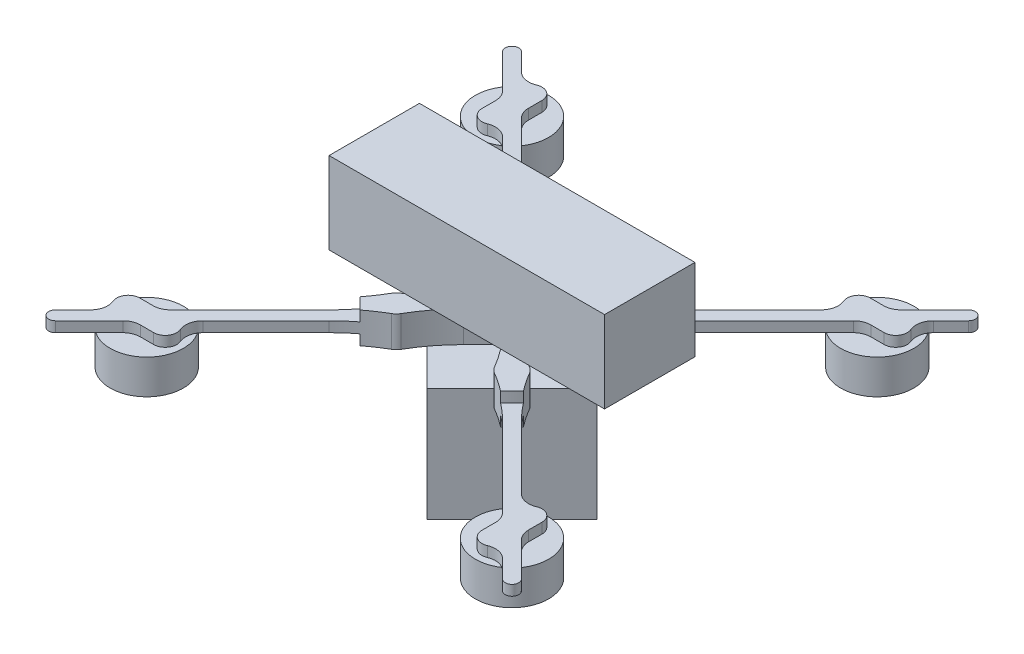
SolidWorks part; units mm, degrees
other "Markup1"
sketch "Sketch7" plane through (54.583, -16.8, -54.583) normal (0.6495, -0.6416, -0.408) x (0.4889, -0.0586, 0.8704)
ref_plane "Front Plane" through (0, 0, 0) normal (0, 0, 1) x (1, 0, 0)
ref_plane "Top Plane" through (0, 0, 0) normal (0, 1, 0) x (1, 0, 0)
ref_plane "Right Plane" through (0, 0, 0) normal (1, 0, 0) x (0, 0, -1)
sketch "Sketch1" plane through (0, 0, 0) normal (0, 1, 0) x (1, 0, 0)
  line L0 (0, 0) -> (0, 62.3643) construction
  line L1 (0, 0) -> (-42.4264, 42.4264) construction
  line L4 (-42.4264, 46.7264) -> (-42.4264, 38.1264) construction
  line L5 (0, 2.192) -> (-51.937, 54.129)
  line L6 (-2.192, 0) -> (-42.9431, 40.751)
  line L7 (-1.096, -1.096) -> (-43.5224, 41.3304) construction
  line L8 (1.096, 1.096) -> (-41.3304, 43.5224) construction
  line L9 (-39.7514, 46.7264) -> (-39.7514, 41.9434)
  line L10 (-45.1014, 38.1264) -> (-45.1014, 42.9094)
  line L11 (-45.1014, 42.9094) -> (-54.129, 51.937)
  line L12 (0, 2.192) -> (0, 0)
  line L13 (0, 0) -> (-2.192, 0)
  arc A2 (-42.4264, 44.0514) -> (-45.051, 47.2431) centre (-42.4264, 46.7264) ccw
  circle A3 centre (-42.4264, 38.1264) radius 2.675
  arc A4 (-51.937, 54.129) -> (-54.129, 51.937) centre (-53.033, 53.033) ccw
  circle A5 centre (-13.435, 13.435) radius 3
  point P6 (-42.4264, 42.4264)
  dimension "D7" = 5.35
  dimension "D8" = 6
  dimension "D1" = 60
  dimension "D2" = 45
  dimension "D3" = 8.6
  dimension "D4" = 1.55
  dimension "D5" = 1.55
  dimension "D6" = 75
  dimension "D9" = 41
extrude "Boss-Extrude1" add sketch "Sketch1" along normal blind 2.4
sketch "Sketch6" plane through (0, 0, 0) normal (0, -1, 0) x (1, 0, 0)
  circle A0 centre (-42.4264, -42.4264) radius 8.5
  dimension "D1" = 17
extrude "Boss-Extrude5" add sketch "Sketch6" along normal blind 8 separate body
fillet "Fillet1" radius 4 4 edges at (-39.7514, 1.2, -41.9434) (-45.051, 1.2, -47.2431) (-45.1014, 1.2, -42.9094) (-39.8018, 1.2, -37.6097)
fillet "Fillet2" radius 40 4 edges at (-10.5228, 1.2, -12.7148) (-14.1553, 1.2, -16.3473) (-12.7148, 1.2, -10.5228) (-16.3473, 1.2, -14.1553)
pattern_circular "CirPattern3" count 4 over 360 about axis through (0, 0, 0) along (0, 1, 0) of bodies 106
pattern_circular "CirPattern1" count 4 over 360 about axis through (0, 0, 0) along (0, 1, 0) of "Boss-Extrude1", "Fillet2", "Fillet1"
sketch "Sketch3" plane through (0, 2.4, 0) normal (0, 1, 0) x (1, 0, 0)
  line L10 (-2.192, 0) -> (-6.7017, -4.5097)
  line L12 (-2.192, 0) -> (-6.7017, -4.5097)
  line L32 (0, 2.192) -> (-4.5097, 6.7017)
  line L33 (-20.1684, 22.3604) -> (-38.5798, 40.7719)
  line L34 (-39.7514, 43.6003) -> (-39.7514, 46.7264)
  line L35 (-47.8541, 50.0461) -> (-51.937, 54.129)
  line L36 (-54.129, 51.937) -> (-46.273, 44.0809)
  line L37 (-45.1014, 41.2525) -> (-45.1014, 38.1264)
  line L38 (-36.9987, 34.8067) -> (-22.3604, 20.1684)
  line L39 (-6.7017, 4.5097) -> (-2.192, 0)
  line L44 (-22.3604, -20.1684) -> (-40.7719, -38.5798)
  line L45 (-22.3604, -20.1684) -> (-40.7719, -38.5798)
  line L46 (-43.6003, -39.7514) -> (-46.7264, -39.7514)
  line L47 (-43.6003, -39.7514) -> (-46.7264, -39.7514)
  line L48 (-50.0461, -47.8541) -> (-54.129, -51.937)
  line L49 (-50.0461, -47.8541) -> (-54.129, -51.937)
  line L50 (-51.937, -54.129) -> (-44.0809, -46.273)
  line L51 (-51.937, -54.129) -> (-44.0809, -46.273)
  line L52 (-41.2525, -45.1014) -> (-38.1264, -45.1014)
  line L53 (-41.2525, -45.1014) -> (-38.1264, -45.1014)
  line L54 (-34.8067, -36.9987) -> (-20.1684, -22.3604)
  line L55 (-34.8067, -36.9987) -> (-20.1684, -22.3604)
  line L56 (-4.5097, -6.7017) -> (0, -2.192)
  line L57 (-4.5097, -6.7017) -> (0, -2.192)
  line L58 (0, -2.192) -> (4.5097, -6.7017)
  line L59 (0, -2.192) -> (4.5097, -6.7017)
  line L60 (20.1684, -22.3604) -> (38.5798, -40.7719)
  line L61 (20.1684, -22.3604) -> (38.5798, -40.7719)
  line L62 (39.7514, -43.6003) -> (39.7514, -46.7264)
  line L63 (39.7514, -43.6003) -> (39.7514, -46.7264)
  line L64 (0, 2.192) -> (-4.5097, 6.7017)
  line L65 (-20.1684, 22.3604) -> (-38.5798, 40.7719)
  line L66 (-39.7514, 43.6003) -> (-39.7514, 46.7264)
  line L67 (-47.8541, 50.0461) -> (-51.937, 54.129)
  line L68 (-54.129, 51.937) -> (-46.273, 44.0809)
  line L69 (-45.1014, 41.2525) -> (-45.1014, 38.1264)
  line L70 (-36.9987, 34.8067) -> (-22.3604, 20.1684)
  line L71 (-6.7017, 4.5097) -> (-2.192, 0)
  line L96 (47.8541, -50.0461) -> (51.937, -54.129)
  line L97 (47.8541, -50.0461) -> (51.937, -54.129)
  line L98 (54.129, -51.937) -> (46.273, -44.0809)
  line L99 (54.129, -51.937) -> (46.273, -44.0809)
  line L100 (45.1014, -41.2525) -> (45.1014, -38.1264)
  line L101 (45.1014, -41.2525) -> (45.1014, -38.1264)
  line L102 (36.9987, -34.8067) -> (22.3604, -20.1684)
  line L103 (36.9987, -34.8067) -> (22.3604, -20.1684)
  line L104 (6.7017, -4.5097) -> (2.192, 0)
  line L105 (6.7017, -4.5097) -> (2.192, 0)
  line L106 (2.192, 0) -> (6.7017, 4.5097)
  line L107 (2.192, 0) -> (6.7017, 4.5097)
  line L108 (22.3604, 20.1684) -> (40.7719, 38.5798)
  line L109 (22.3604, 20.1684) -> (40.7719, 38.5798)
  line L110 (43.6003, 39.7514) -> (46.7264, 39.7514)
  line L111 (43.6003, 39.7514) -> (46.7264, 39.7514)
  line L112 (50.0461, 47.8541) -> (54.129, 51.937)
  line L113 (50.0461, 47.8541) -> (54.129, 51.937)
  line L114 (51.937, 54.129) -> (44.0809, 46.273)
  line L115 (51.937, 54.129) -> (44.0809, 46.273)
  line L116 (41.2525, 45.1014) -> (38.1264, 45.1014)
  line L117 (41.2525, 45.1014) -> (38.1264, 45.1014)
  line L118 (34.8067, 36.9987) -> (20.1684, 22.3604)
  line L119 (34.8067, 36.9987) -> (20.1684, 22.3604)
  line L120 (4.5097, 6.7017) -> (0, 2.192)
  line L121 (4.5097, 6.7017) -> (0, 2.192)
  circle A0 centre (0, 0) radius 25.002
  arc A53 (-10.839, 14.9386) -> (-4.5097, 6.7017) centre (23.7746, 34.986) ccw
  arc A54 (-10.839, 14.9386) -> (-11.9315, 16.0311) centre (-13.435, 13.435) ccw
  arc A55 (-20.1684, 22.3604) -> (-11.9315, 16.0311) centre (8.1159, 50.6447) ccw
  arc A56 (-39.7514, 43.6003) -> (-38.5798, 40.7719) centre (-35.7514, 43.6003) ccw
  arc A57 (-39.7514, 46.7264) -> (-43.4681, 49.1903) centre (-42.4264, 46.7264) ccw
  arc A58 (-47.8541, 50.0461) -> (-43.4681, 49.1903) centre (-45.0257, 52.8745) ccw
  arc A59 (-51.937, 54.129) -> (-54.129, 51.937) centre (-53.033, 53.033) ccw
  arc A60 (-45.1014, 41.2525) -> (-46.273, 44.0809) centre (-49.1014, 41.2525) ccw
  arc A61 (-45.1014, 38.1264) -> (-41.3848, 35.6625) centre (-42.4264, 38.1264) ccw
  arc A62 (-36.9987, 34.8067) -> (-41.3848, 35.6625) centre (-39.8272, 31.9783) ccw
  arc A63 (-16.0311, 11.9315) -> (-22.3604, 20.1684) centre (-50.6447, -8.1159) ccw
  arc A64 (-16.0311, 11.9315) -> (-14.9386, 10.839) centre (-13.435, 13.435) ccw
  arc A65 (-6.7017, 4.5097) -> (-14.9386, 10.839) centre (-34.986, -23.7746) ccw
  arc A66 (-14.9386, -10.839) -> (-6.7017, -4.5097) centre (-34.986, 23.7746) ccw
  arc A67 (-14.9386, -10.839) -> (-6.7017, -4.5097) centre (-34.986, 23.7746) ccw
  arc A68 (-14.9386, -10.839) -> (-16.0311, -11.9315) centre (-13.435, -13.435) ccw
  arc A69 (-14.9386, -10.839) -> (-16.0311, -11.9315) centre (-13.435, -13.435) ccw
  arc A70 (-22.3604, -20.1684) -> (-16.0311, -11.9315) centre (-50.6447, 8.1159) ccw
  arc A71 (-22.3604, -20.1684) -> (-16.0311, -11.9315) centre (-50.6447, 8.1159) ccw
  arc A72 (-43.6003, -39.7514) -> (-40.7719, -38.5798) centre (-43.6003, -35.7514) ccw
  arc A73 (-43.6003, -39.7514) -> (-40.7719, -38.5798) centre (-43.6003, -35.7514) ccw
  arc A74 (-46.7264, -39.7514) -> (-49.1903, -43.4681) centre (-46.7264, -42.4264) ccw
  arc A75 (-46.7264, -39.7514) -> (-49.1903, -43.4681) centre (-46.7264, -42.4264) ccw
  arc A76 (-50.0461, -47.8541) -> (-49.1903, -43.4681) centre (-52.8745, -45.0257) ccw
  arc A77 (-50.0461, -47.8541) -> (-49.1903, -43.4681) centre (-52.8745, -45.0257) ccw
  arc A78 (-54.129, -51.937) -> (-51.937, -54.129) centre (-53.033, -53.033) ccw
  arc A79 (-54.129, -51.937) -> (-51.937, -54.129) centre (-53.033, -53.033) ccw
  arc A80 (-41.2525, -45.1014) -> (-44.0809, -46.273) centre (-41.2525, -49.1014) ccw
  arc A81 (-41.2525, -45.1014) -> (-44.0809, -46.273) centre (-41.2525, -49.1014) ccw
  arc A82 (-38.1264, -45.1014) -> (-35.6625, -41.3848) centre (-38.1264, -42.4264) ccw
  arc A83 (-38.1264, -45.1014) -> (-35.6625, -41.3848) centre (-38.1264, -42.4264) ccw
  arc A84 (-34.8067, -36.9987) -> (-35.6625, -41.3848) centre (-31.9783, -39.8272) ccw
  arc A85 (-34.8067, -36.9987) -> (-35.6625, -41.3848) centre (-31.9783, -39.8272) ccw
  arc A86 (-11.9315, -16.0311) -> (-20.1684, -22.3604) centre (8.1159, -50.6447) ccw
  arc A87 (-11.9315, -16.0311) -> (-20.1684, -22.3604) centre (8.1159, -50.6447) ccw
  arc A88 (-11.9315, -16.0311) -> (-10.839, -14.9386) centre (-13.435, -13.435) ccw
  arc A89 (-11.9315, -16.0311) -> (-10.839, -14.9386) centre (-13.435, -13.435) ccw
  arc A90 (-4.5097, -6.7017) -> (-10.839, -14.9386) centre (23.7746, -34.986) ccw
  arc A91 (-4.5097, -6.7017) -> (-10.839, -14.9386) centre (23.7746, -34.986) ccw
  arc A92 (10.839, -14.9386) -> (4.5097, -6.7017) centre (-23.7746, -34.986) ccw
  arc A93 (10.839, -14.9386) -> (4.5097, -6.7017) centre (-23.7746, -34.986) ccw
  arc A94 (10.839, -14.9386) -> (11.9315, -16.0311) centre (13.435, -13.435) ccw
  arc A95 (10.839, -14.9386) -> (11.9315, -16.0311) centre (13.435, -13.435) ccw
  arc A96 (20.1684, -22.3604) -> (11.9315, -16.0311) centre (-8.1159, -50.6447) ccw
  arc A97 (20.1684, -22.3604) -> (11.9315, -16.0311) centre (-8.1159, -50.6447) ccw
  arc A98 (39.7514, -43.6003) -> (38.5798, -40.7719) centre (35.7514, -43.6003) ccw
  arc A99 (39.7514, -43.6003) -> (38.5798, -40.7719) centre (35.7514, -43.6003) ccw
  arc A100 (39.7514, -46.7264) -> (43.4681, -49.1903) centre (42.4264, -46.7264) ccw
  arc A101 (39.7514, -46.7264) -> (43.4681, -49.1903) centre (42.4264, -46.7264) ccw
  arc A102 (47.8541, -50.0461) -> (43.4681, -49.1903) centre (45.0257, -52.8745) ccw
  arc A103 (47.8541, -50.0461) -> (43.4681, -49.1903) centre (45.0257, -52.8745) ccw
  arc A104 (51.937, -54.129) -> (54.129, -51.937) centre (53.033, -53.033) ccw
  arc A105 (-10.839, 14.9386) -> (-4.5097, 6.7017) centre (23.7746, 34.986) ccw
  arc A106 (-10.839, 14.9386) -> (-11.9315, 16.0311) centre (-13.435, 13.435) ccw
  arc A107 (-20.1684, 22.3604) -> (-11.9315, 16.0311) centre (8.1159, 50.6447) ccw
  arc A108 (-39.7514, 43.6003) -> (-38.5798, 40.7719) centre (-35.7514, 43.6003) ccw
  arc A109 (-39.7514, 46.7264) -> (-43.4681, 49.1903) centre (-42.4264, 46.7264) ccw
  arc A110 (-47.8541, 50.0461) -> (-43.4681, 49.1903) centre (-45.0257, 52.8745) ccw
  arc A111 (-51.937, 54.129) -> (-54.129, 51.937) centre (-53.033, 53.033) ccw
  arc A112 (-45.1014, 41.2525) -> (-46.273, 44.0809) centre (-49.1014, 41.2525) ccw
  arc A113 (-45.1014, 38.1264) -> (-41.3848, 35.6625) centre (-42.4264, 38.1264) ccw
  arc A114 (-36.9987, 34.8067) -> (-41.3848, 35.6625) centre (-39.8272, 31.9783) ccw
  arc A115 (-16.0311, 11.9315) -> (-22.3604, 20.1684) centre (-50.6447, -8.1159) ccw
  arc A116 (-16.0311, 11.9315) -> (-14.9386, 10.839) centre (-13.435, 13.435) ccw
  arc A117 (-6.7017, 4.5097) -> (-14.9386, 10.839) centre (-34.986, -23.7746) ccw
  arc A157 (51.937, -54.129) -> (54.129, -51.937) centre (53.033, -53.033) ccw
  arc A158 (45.1014, -41.2525) -> (46.273, -44.0809) centre (49.1014, -41.2525) ccw
  arc A159 (45.1014, -41.2525) -> (46.273, -44.0809) centre (49.1014, -41.2525) ccw
  arc A160 (45.1014, -38.1264) -> (41.3848, -35.6625) centre (42.4264, -38.1264) ccw
  arc A161 (45.1014, -38.1264) -> (41.3848, -35.6625) centre (42.4264, -38.1264) ccw
  arc A162 (36.9987, -34.8067) -> (41.3848, -35.6625) centre (39.8272, -31.9783) ccw
  arc A163 (36.9987, -34.8067) -> (41.3848, -35.6625) centre (39.8272, -31.9783) ccw
  arc A164 (16.0311, -11.9315) -> (22.3604, -20.1684) centre (50.6447, 8.1159) ccw
  arc A165 (16.0311, -11.9315) -> (22.3604, -20.1684) centre (50.6447, 8.1159) ccw
  arc A166 (16.0311, -11.9315) -> (14.9386, -10.839) centre (13.435, -13.435) ccw
  arc A167 (16.0311, -11.9315) -> (14.9386, -10.839) centre (13.435, -13.435) ccw
  arc A168 (6.7017, -4.5097) -> (14.9386, -10.839) centre (34.986, 23.7746) ccw
  arc A169 (6.7017, -4.5097) -> (14.9386, -10.839) centre (34.986, 23.7746) ccw
  arc A170 (14.9386, 10.839) -> (6.7017, 4.5097) centre (34.986, -23.7746) ccw
  arc A171 (14.9386, 10.839) -> (6.7017, 4.5097) centre (34.986, -23.7746) ccw
  arc A172 (14.9386, 10.839) -> (16.0311, 11.9315) centre (13.435, 13.435) ccw
  arc A173 (14.9386, 10.839) -> (16.0311, 11.9315) centre (13.435, 13.435) ccw
  arc A174 (22.3604, 20.1684) -> (16.0311, 11.9315) centre (50.6447, -8.1159) ccw
  arc A175 (22.3604, 20.1684) -> (16.0311, 11.9315) centre (50.6447, -8.1159) ccw
  arc A176 (43.6003, 39.7514) -> (40.7719, 38.5798) centre (43.6003, 35.7514) ccw
  arc A177 (43.6003, 39.7514) -> (40.7719, 38.5798) centre (43.6003, 35.7514) ccw
  arc A178 (46.7264, 39.7514) -> (49.1903, 43.4681) centre (46.7264, 42.4264) ccw
  arc A179 (46.7264, 39.7514) -> (49.1903, 43.4681) centre (46.7264, 42.4264) ccw
  arc A180 (50.0461, 47.8541) -> (49.1903, 43.4681) centre (52.8745, 45.0257) ccw
  arc A181 (50.0461, 47.8541) -> (49.1903, 43.4681) centre (52.8745, 45.0257) ccw
  arc A182 (54.129, 51.937) -> (51.937, 54.129) centre (53.033, 53.033) ccw
  arc A183 (54.129, 51.937) -> (51.937, 54.129) centre (53.033, 53.033) ccw
  arc A184 (41.2525, 45.1014) -> (44.0809, 46.273) centre (41.2525, 49.1014) ccw
  arc A185 (41.2525, 45.1014) -> (44.0809, 46.273) centre (41.2525, 49.1014) ccw
  arc A186 (38.1264, 45.1014) -> (35.6625, 41.3848) centre (38.1264, 42.4264) ccw
  arc A187 (38.1264, 45.1014) -> (35.6625, 41.3848) centre (38.1264, 42.4264) ccw
  arc A188 (34.8067, 36.9987) -> (35.6625, 41.3848) centre (31.9783, 39.8272) ccw
  arc A189 (34.8067, 36.9987) -> (35.6625, 41.3848) centre (31.9783, 39.8272) ccw
  arc A190 (11.9315, 16.0311) -> (20.1684, 22.3604) centre (-8.1159, 50.6447) ccw
  arc A191 (11.9315, 16.0311) -> (20.1684, 22.3604) centre (-8.1159, 50.6447) ccw
  arc A192 (11.9315, 16.0311) -> (10.839, 14.9386) centre (13.435, 13.435) ccw
  arc A193 (11.9315, 16.0311) -> (10.839, 14.9386) centre (13.435, 13.435) ccw
  arc A194 (4.5097, 6.7017) -> (10.839, 14.9386) centre (-23.7746, 34.986) ccw
  arc A195 (4.5097, 6.7017) -> (10.839, 14.9386) centre (-23.7746, 34.986) ccw
  dimension "D1" = 0
extrude "Boss-Extrude2" add sketch "Sketch3" along normal blind 2.4 and the other way blind 4.8 contours A195 L121 L64 A105 A106 A107 A0 A115 A116 A117 L71 L12 A67 A69 A71 A87 A89 A91 L57 L59 A93 A95 A97 A165 A167 A169 L105 L107 A171 A173 A175 A191 A193
sketch "Sketch4" plane through (0, -2.4, 0) normal (0, -1, 0) x (1, 0, 0)
  line L1 (-19.799, 0) -> (0, -19.799)
  line L2 (-19.799, 0) -> (0, 19.799)
  line L3 (0, 19.799) -> (19.799, 0)
  line L4 (0, -19.799) -> (19.799, 0)
  line L5 (-19.799, 0) -> (19.799, 0) construction
  line L6 (0, 19.799) -> (0, -19.799) construction
  point P0 (0, 0)
  dimension "D1" = 28
extrude "Boss-Extrude3" add sketch "Sketch4" along normal blind 26.4 separate body
sketch "Sketch5" plane through (0, 4.8, 0) normal (0, 1, 0) x (1, 0, 0)
  line L1 (-32, -10.5) -> (32, -10.5)
  line L2 (-32, -10.5) -> (-32, 10.5)
  line L3 (-32, 10.5) -> (32, 10.5)
  line L4 (32, -10.5) -> (32, 10.5)
  line L5 (-32, -10.5) -> (32, 10.5) construction
  line L6 (-32, 10.5) -> (32, -10.5) construction
  point P0 (0, 0)
  dimension "D1" = 21
  dimension "D2" = 64
extrude "Boss-Extrude4" add sketch "Sketch5" along normal blind 19 separate body
